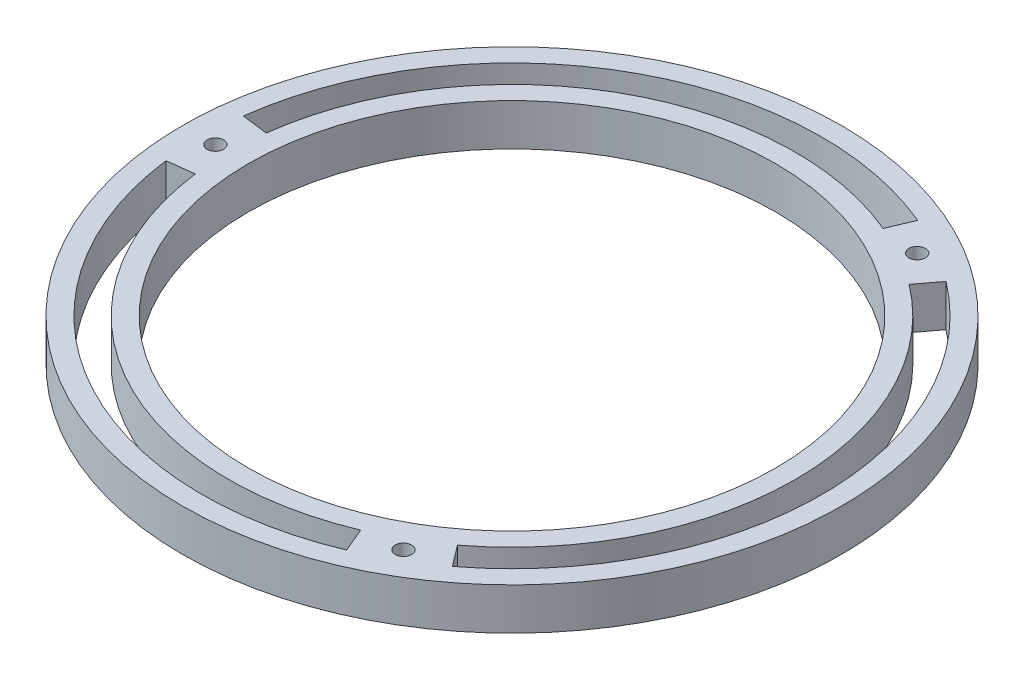
SolidWorks part; units mm, degrees
ref_plane "Front Plane" through (0, 0, 0) normal (0, 0, 1) x (1, 0, 0)
ref_plane "Top Plane" through (0, 0, 0) normal (0, 1, 0) x (1, 0, 0)
ref_plane "Right Plane" through (0, 0, 0) normal (1, 0, 0) x (0, 0, -1)
sketch "Sketch1" plane through (0, 0, 0) normal (0, 1, 0) x (1, 0, 0)
  line L0 (-50, 0) -> (50, 0) construction
  line L1 (-25, 43.3013) -> (25, -43.3013) construction
  line L2 (-25, -43.3013) -> (25, 43.3013) construction
  line L3 (30.2166, 39.8366) -> (24.1733, 31.8693)
  line L4 (19.3913, 46.0866) -> (15.513, 36.8693)
  line L5 (30.2166, -39.8366) -> (24.1733, -31.8693)
  line L6 (19.3913, -46.0866) -> (15.513, -36.8693)
  line L7 (-49.6078, 6.25) -> (-39.6863, 5)
  line L8 (-49.6078, -6.25) -> (-39.6863, -5)
  line L9 (0, 0) -> (15.513, 36.8693) construction
  line L10 (0, 0) -> (24.1733, 31.8693) construction
  line L11 (0, 0) -> (24.1733, -31.8693) construction
  line L12 (0, 0) -> (15.513, -36.8693) construction
  line L13 (0, 0) -> (-39.6863, 5) construction
  line L14 (-39.6863, -5) -> (0, 0) construction
  circle A0 centre (0, 0) radius 50
  circle A1 centre (0, 0) radius 47
  circle A2 centre (0, 0) radius 43
  circle A3 centre (0, 0) radius 40
  point P10 (0, 0)
  point P14 (0, 0)
  point P17 (0, 0)
  dimension "D1" = 100
  dimension "D2" = 3
  dimension "D5" = 60
  dimension "D6" = 60
  dimension "D7" = 5
  dimension "D8" = 5
  dimension "D9" = 5
  dimension "D10" = 5
  dimension "D11" = 5
  dimension "D12" = 5
  dimension "D3" = 4
  dimension "D4" = 3
extrude "Boss-Extrude1" add sketch "Sketch1" along normal blind 6.35 contours A1 L5 A0 L3 | A3 L5 A2 L3 | A3 L6 A2 L5 | A2 L6 A1 L5 | A1 L6 A0 L5 | A1 L8 A0 L6 | A3 L8 A2 L6 | A3 L7 A2 L8 | A2 L7 A1 L8 | A1 L7 A0 L8 | A1 L4 A0 L7 | A3 L4 A2 L7 | A3 L3 A2 L4 | A2 L3 A1 L4 | A1 L3 A0 L4
sketch "Sketch2" plane through (0, 6.35, 0) normal (0, 1, 0) x (1, 0, 0)
  line L1 (25, 43.3013) -> (20, 34.641) construction
  line L2 (20, -34.641) -> (25, -43.3013) construction
  line L3 (0, 0) -> (25.9863, -34.2595) construction
  line L4 (0, 0) -> (-40, 0) construction
  line L6 (0, 0) -> (20, -34.641) construction
  line L7 (-40, 0) -> (-50, 0) construction
  line L8 (0, 0) -> (20, 34.641) construction
  line L9 (0, 0) -> (16.6765, 39.6345) construction
  circle A0 centre (-45, 0) radius 1.25
  circle A1 centre (22.5, -38.9711) radius 1.25
  circle A2 centre (22.5, 38.9711) radius 1.25
  circle A3 centre (0, 0) radius 40 construction
  circle A4 centre (0, 0) radius 50 construction
  dimension "D1" = 2.5
  dimension "D2" = 5
  dimension "D3" = 5
extrude "M3-tap-holes" cut sketch "Sketch2" against normal up to next
